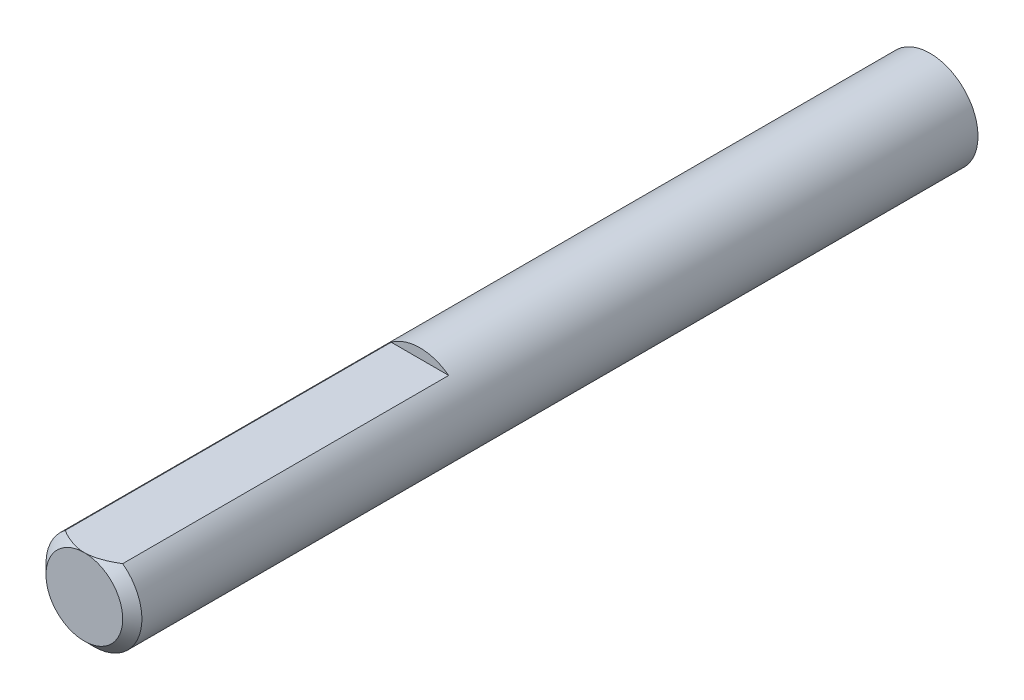
SolidWorks part; units mm, degrees
material "Acero aleado"
ref_plane "Alzado" through (0, 0, 0) normal (0, 0, 1) x (1, 0, 0)
ref_plane "Planta" through (0, 0, 0) normal (0, 1, 0) x (1, 0, 0)
ref_plane "Vista lateral" through (0, 0, 0) normal (1, 0, 0) x (0, 0, -1)
other "Исполнения"
sketch "Croquis1" plane through (0, 0, 0) normal (0, 0, 1) x (1, 0, 0)
  circle A0 centre (0, 0) radius 2.5
  dimension "D1" = 5
extrude "Saliente-Extruir1" add sketch "Croquis1" along normal blind 44.1
sketch "Croquis2" plane through (0, 0, 44.1) normal (0, 0, 1) x (1, 0, 0)
  circle A0 centre (0, 0) radius 1
  dimension "D1" = 2
extrude "Cortar-Extruir1" [suppressed] cut sketch "Croquis2" against normal blind 10
fillet "Redondeo1" radius 0.5 1 edges at (2.5, 0, 44.1) profile chamfer
sketch "Эскиз1" plane through (0, 0, 44.1) normal (0, 0, 1) x (1, 0, 0)
  line L1 (-2.5441, 2) -> (2.7286, 2)
  line L2 (-2.5441, 2) -> (-2.5441, 3.9598)
  line L3 (-2.5441, 3.9598) -> (2.7286, 3.9598)
  line L4 (2.7286, 2) -> (2.7286, 3.9598)
  circle A0 centre (0, 0) radius 2.5 construction
  dimension "D1" = 4.5
extrude "Вырез-Вытянуть1" cut sketch "Эскиз1" against normal blind 17.5
